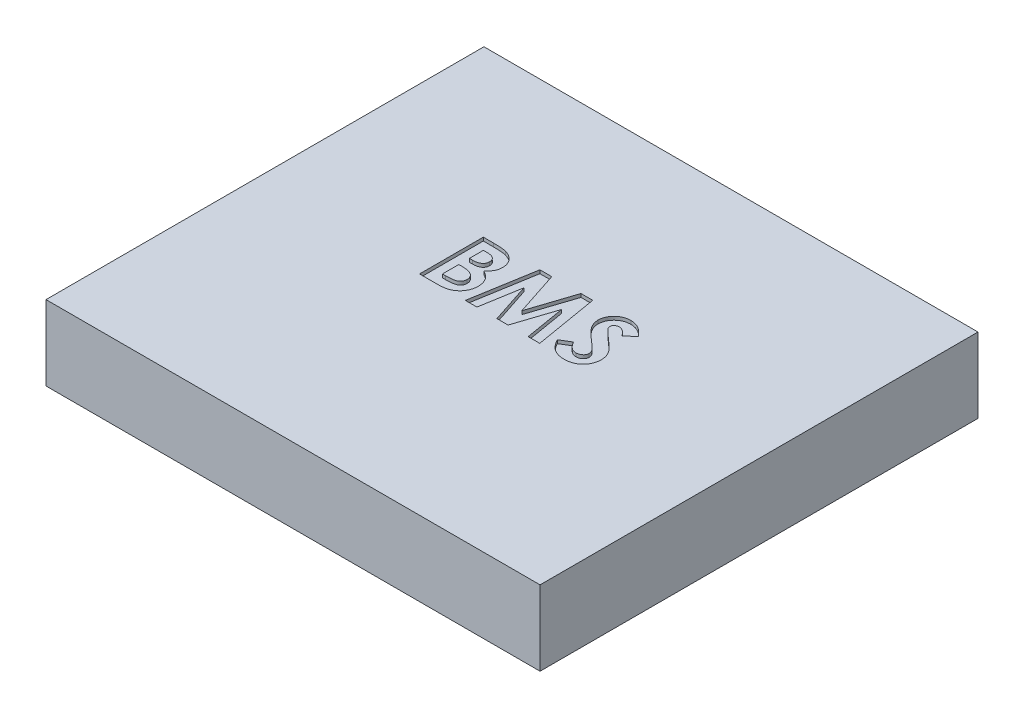
SolidWorks part; units mm, degrees
ref_plane "Front Plane" through (0, 0, 0) normal (0, 0, 1) x (1, 0, 0)
ref_plane "Top Plane" through (0, 0, 0) normal (0, 1, 0) x (1, 0, 0)
ref_plane "Right Plane" through (0, 0, 0) normal (1, 0, 0) x (0, 0, -1)
sketch "Sketch1" plane through (0, 0, 0) normal (0, 1, 0) x (1, 0, 0)
  line L1 (-58.1, -51.5) -> (58.1, -51.5)
  line L2 (-58.1, -51.5) -> (-58.1, 51.5)
  line L3 (-58.1, 51.5) -> (58.1, 51.5)
  line L4 (58.1, -51.5) -> (58.1, 51.5)
  line L5 (0, 51.5) -> (0, -51.5) construction
  line L6 (-58.1, 0) -> (58.1, 0) construction
  point P0 (0, 0)
  dimension "D1" = 103
  dimension "D2" = 116.2
extrude "Boss-Extrude1" add sketch "Sketch1" along normal blind 17.6
sketch "Sketch2" plane through (0, 17.6, 0) normal (0, 1, 0) x (1, 0, 0)
  text T0 "<b>BMS</b>" font "Century Gothic" height 15
extrude "Cut-Extrude1" cut sketch "Sketch2" against normal blind 0.8
